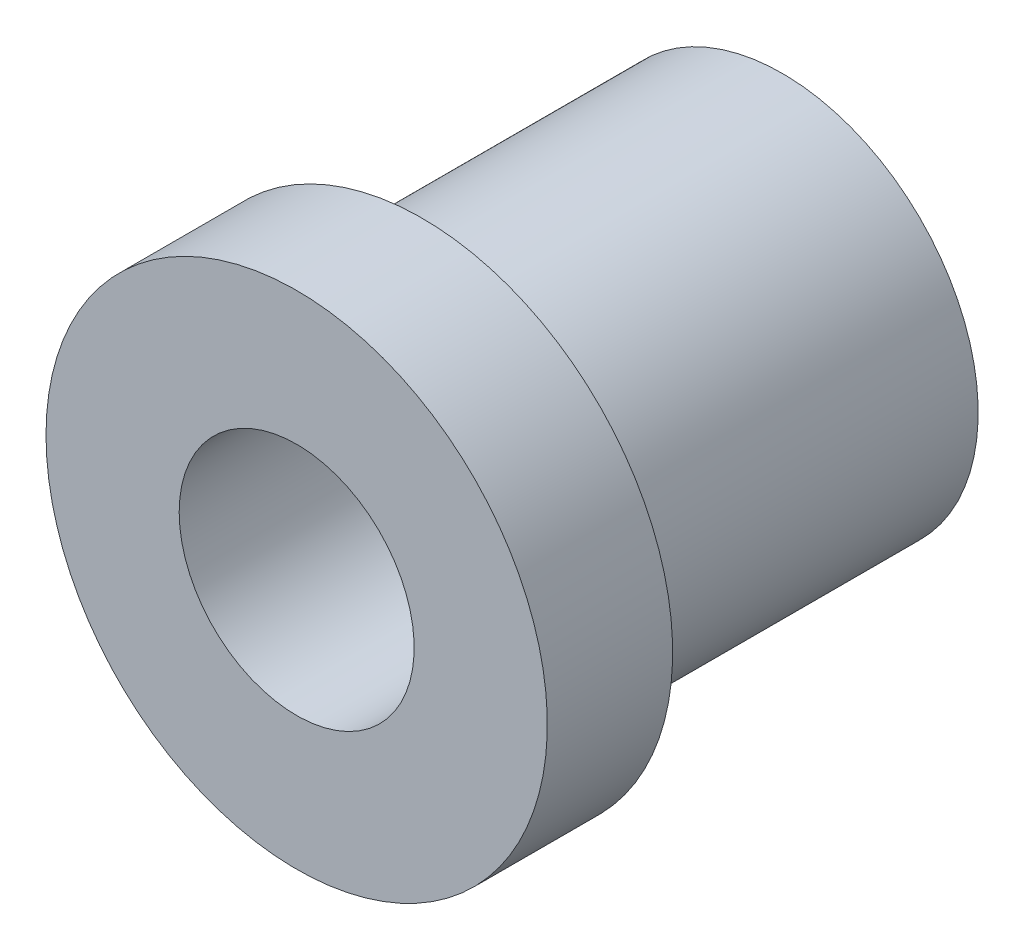
SolidWorks part; units mm, degrees
material "Сталь 45 ГОСТ 1050-88"
ref_plane "Front Plane" through (0, 0, 0) normal (0, 0, 1) x (1, 0, 0)
ref_plane "Top Plane" through (0, 0, 0) normal (0, 1, 0) x (1, 0, 0)
ref_plane "Right Plane" through (0, 0, 0) normal (1, 0, 0) x (0, 0, -1)
sketch "Skizze1" plane through (0, 0, 0) normal (0, 1, 0) x (1, 0, 0)
  line L0 (1.5, -0.0038) -> (-7.5, -0.0038)
  line L1 (1.5, -0.0038) -> (-16, -0.0038)
  line L2 (1.5, -0.0038) -> (7.5, -0.0038)
  line L3 (1.5, -0.0038) -> (16, -0.0038)
  line L4 (-12.5, 7.9962) -> (-12.5, 30.9962)
  line L5 (-12.5, 30.9962) -> (12.5, 30.9962)
  line L6 (12.5, 30.9962) -> (12.5, 7.9962)
  line L7 (-7.5, -0.0038) -> (-7.5, 30.9962)
  line L8 (7.5, -0.0038) -> (7.5, 30.9962)
  line L9 (0, 31.8184) -> (0, -1.8638) construction
  line L10 (16, 7.9962) -> (12.5, 7.9962)
  line L11 (-16, 2.9729) -> (-16, -0.0038)
  line L12 (-16, -0.0038) -> (-16, 7.9962)
  line L13 (-16, 7.9962) -> (-12.5, 7.9962)
  line L14 (16, -0.0038) -> (16, 7.9962)
  line L15 (16, 2.9729) -> (16, -0.0038)
revolve "Rotation1" add sketch "Skizze1" angle 360 about L9
